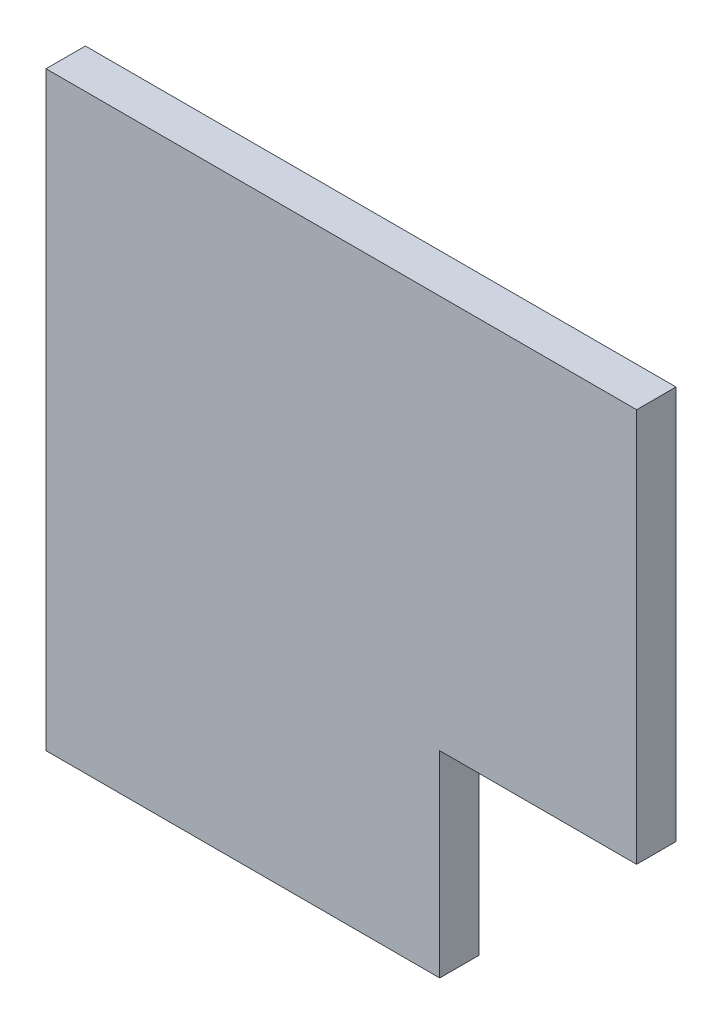
SolidWorks part; units mm, degrees
material "PBT General Purpose"
ref_plane "Front Plane" through (0, 0, 0) normal (0, 0, 1) x (1, 0, 0)
ref_plane "Top Plane" through (0, 0, 0) normal (0, 1, 0) x (1, 0, 0)
ref_plane "Right Plane" through (0, 0, 0) normal (1, 0, 0) x (0, 0, -1)
sketch "Sketch1" plane through (0, 0, 0) normal (0, 0, 1) x (1, 0, 0)
  line L0 (0, 0) -> (0, 1)
  line L1 (0, 1) -> (-1.5, 1)
  line L2 (-1.5, 1) -> (-1.5, -0.5)
  line L3 (-1.5, -0.5) -> (-0.5, -0.5)
  line L4 (-0.5, -0.5) -> (-0.5, 0)
  line L5 (-0.5, 0) -> (0, 0)
  dimension "D1" = 1
  dimension "D2" = 0.5
  dimension "D3" = 0.5
  dimension "D4" = 1
extrude "Boss-Extrude1" add sketch "Sketch1" along normal mid plane 0.1
